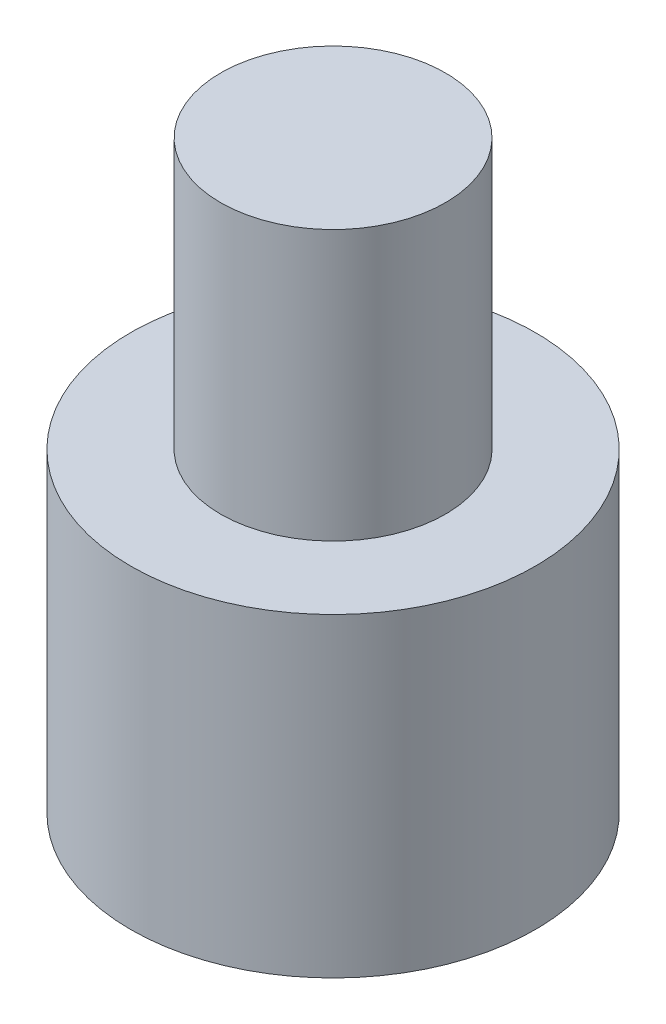
SolidWorks part; units mm, degrees
ref_plane "Front Plane" through (0, 0, 0) normal (0, 0, 1) x (1, 0, 0)
ref_plane "Top Plane" through (0, 0, 0) normal (0, 1, 0) x (1, 0, 0)
ref_plane "Right Plane" through (0, 0, 0) normal (1, 0, 0) x (0, 0, -1)
sketch "Sketch1" plane through (0, 0, 0) normal (0, 1, 0) x (1, 0, 0)
  circle A0 centre (0, 0) radius 4.5
  dimension "D1" = 9
extrude "Boss-Extrude1" add sketch "Sketch1" along normal blind 7 contours A0
sketch "Sketch2" plane through (0, 0, 0) normal (0, -1, 0) x (1, 0, 0)
  circle A0 centre (0, 0) radius 1.675
  dimension "D1" = 3.35
extrude "Cut-Extrude1" cut sketch "Sketch2" against normal blind 6
sketch "Sketch3" plane through (0, 7, 0) normal (0, 1, 0) x (1, 0, 0)
  circle A0 centre (0, 0) radius 2.5
  dimension "D1" = 5
extrude "Boss-Extrude2" add sketch "Sketch3" along normal blind 6
